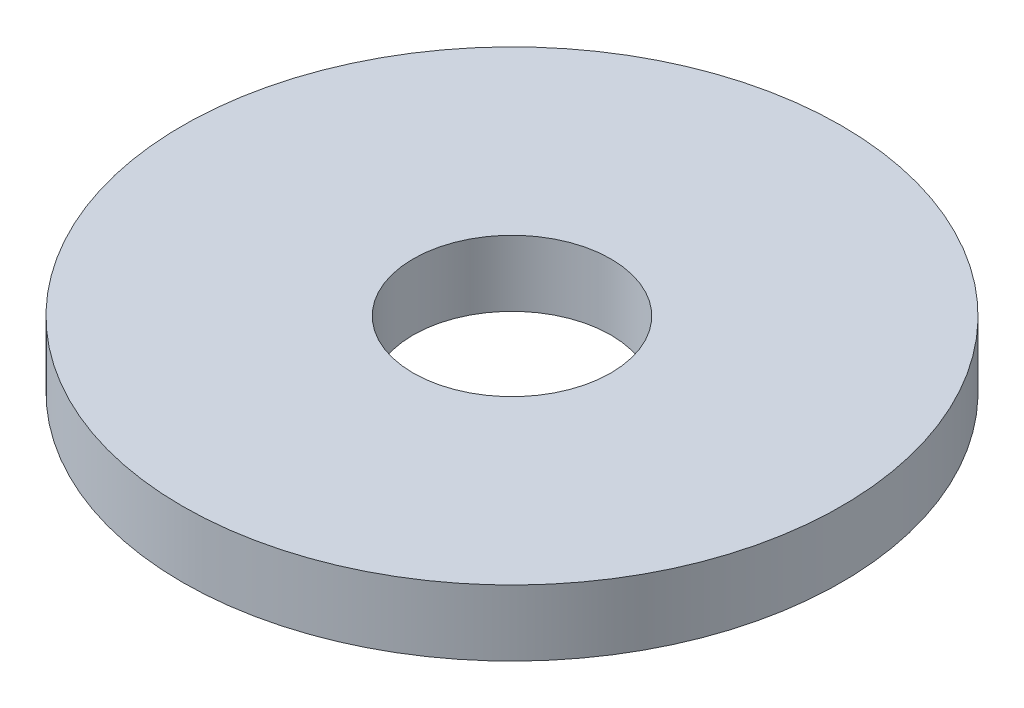
SolidWorks part; units mm, degrees
ref_plane "Front Plane" through (0, 0, 0) normal (0, 0, 1) x (1, 0, 0)
ref_plane "Top Plane" through (0, 0, 0) normal (0, 1, 0) x (1, 0, 0)
ref_plane "Right Plane" through (0, 0, 0) normal (1, 0, 0) x (0, 0, -1)
sketch "Sketch1" plane through (0, 0, 0) normal (0, 1, 0) x (1, 0, 0)
  circle A4 centre (12.8686, -5) radius 5
  circle A5 centre (12.8686, -5) radius 1.5
  dimension "D5" = 10
  dimension "D6" = 3
extrude "Boss-Extrude1" add sketch "Sketch1" along normal blind 1
